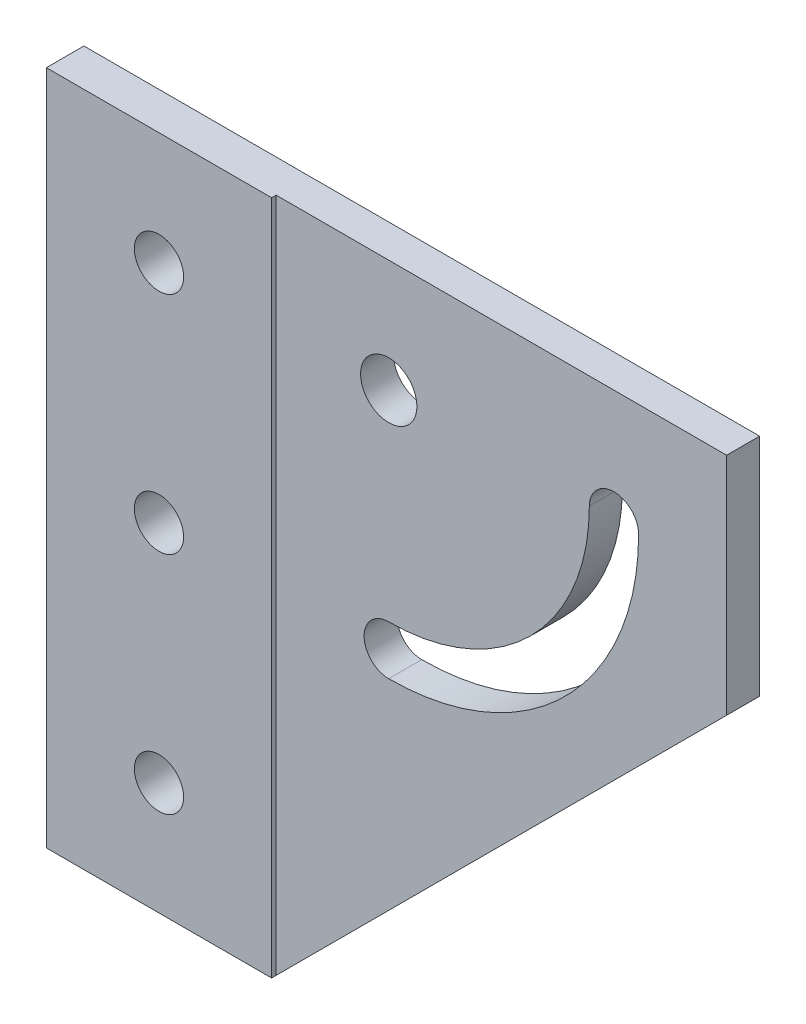
SolidWorks part; units mm, degrees
material "6105-T5 Aluminum"
ref_plane "Front Plane" through (0, 0, 0) normal (0, 0, 1) x (1, 0, 0)
ref_plane "Top Plane" through (0, 0, 0) normal (0, 1, 0) x (1, 0, 0)
ref_plane "Right Plane" through (0, 0, 0) normal (1, 0, 0) x (0, 0, -1)
ref_plane "Plane1" through (0, 0, -17.1983) normal (0, 0, -1) x (-1, 0, 0)
sketch "Sketch1" plane through (0, 0, -17.1983) normal (0, 0, -1) x (-1, 0, 0)
  line L0 (-47.8626, 85.0047) -> (-47.8626, 46.9047)
  line L1 (-47.8626, 46.9047) -> (28.3374, -29.2953)
  line L2 (28.3374, -29.2953) -> (66.4374, -29.2953)
  line L3 (66.4374, -29.2953) -> (66.4374, 85.0047)
  line L4 (66.4374, 85.0047) -> (-47.8626, 85.0047)
  dimension "D1" = 76.2
  dimension "D2" = 114.3
  dimension "D3" = 76.2
  dimension "D4" = 114.3
extrude "Boss-Extrude1" add sketch "Sketch1" against normal blind 5.588
sketch "Sketch2" plane through (0, 0, -11.6103) normal (0, 0, 1) x (1, 0, 0)
  line L0 (-66.4374, -29.2953) -> (-66.4374, 85.0047)
  line L1 (-66.4374, 85.0047) -> (-28.3374, 85.0047)
  line L2 (-28.3374, 85.0047) -> (-28.3374, -29.2953)
  line L3 (-28.3374, -29.2953) -> (-66.4374, -29.2953)
  line L4 (-66.4374, -29.2953) -> (-66.4374, 85.0047) construction
  line L5 (-28.3374, -29.2953) -> (-66.4374, -29.2953) construction
  dimension "D1" = 38.1
  dimension "D2" = 114.3
extrude "Boss-Extrude2" add sketch "Sketch2" along normal blind 0.762
sketch "Sketch3" plane through (0, 0, -11.6103) normal (0, 0, 1) x (1, 0, 0)
  line L0 (-28.3374, -29.2953) -> (-28.3374, 85.0047) construction
  arc A0 (-9.2874, 23.6891) -> (32.9782, 65.9547) centre (-9.2874, 65.9547) ccw
  arc A1 (32.9782, 65.9547) -> (24.647, 65.9547) centre (28.8126, 65.9547) ccw
  arc A2 (24.647, 65.9547) -> (-9.2874, 32.0203) centre (-9.2874, 65.9547) cw
  arc A3 (-9.2874, 32.0203) -> (-9.2874, 23.6891) centre (-9.2874, 27.8547) ccw
  dimension "D1" = 42.2656
  dimension "D2" = 4.1656
  dimension "D3" = 52.9844
  dimension "D4" = 52.9844
extrude "Cut-Extrude1" cut sketch "Sketch3" against normal through all
hole_wizard "Hole1" positions "Sketch5" profile "Sketch4" legacy
sketch "Sketch5" plane through (0, 0, -10.8483) normal (0, 0, 1) x (1, 0, 0)
  point P0 (-47.3874, -10.2453)
sketch "Sketch4" plane through (-47.3874, -10.2453, -10.8483) normal (1, 0, 0) x (0, -1, 0)
  line L0 (0, 0) -> (0, 6.35)
  line L1 (0, 6.35) -> (4.1656, 6.35)
  line L2 (4.1656, 6.35) -> (4.1656, 0)
  line L3 (4.1656, 0) -> (0, 0)
  line L4 (0, 110) -> (0, -10) construction
  dimension "Diameter" = 8.3312
  dimension "Depth" = 6.35
hole_wizard "Hole2" positions "Sketch7" profile "Sketch6" legacy
sketch "Sketch7" plane through (0, 0, -10.8483) normal (0, 0, 1) x (1, 0, 0)
  point P0 (-47.3874, 65.9547)
sketch "Sketch6" plane through (-47.3874, 65.9547, -10.8483) normal (1, 0, 0) x (0, -1, 0)
  line L0 (0, 0) -> (0, 6.35)
  line L1 (0, 6.35) -> (4.1656, 6.35)
  line L2 (4.1656, 6.35) -> (4.1656, 0)
  line L3 (4.1656, 0) -> (0, 0)
  line L4 (0, 110) -> (0, -10) construction
  dimension "Diameter" = 8.3312
  dimension "Depth" = 6.35
hole_wizard "Hole3" positions "Sketch9" profile "Sketch8" legacy
sketch "Sketch9" plane through (0, 0, -10.8483) normal (0, 0, 1) x (1, 0, 0)
  point P0 (-47.3874, 27.8547)
sketch "Sketch8" plane through (-47.3874, 27.8547, -10.8483) normal (1, 0, 0) x (0, -1, 0)
  line L0 (0, 0) -> (0, 6.35)
  line L1 (0, 6.35) -> (4.1656, 6.35)
  line L2 (4.1656, 6.35) -> (4.1656, 0)
  line L3 (4.1656, 0) -> (0, 0)
  line L4 (0, 110) -> (0, -10) construction
  dimension "Diameter" = 8.3312
  dimension "Depth" = 6.35
hole_wizard "M8 Clearance Hole1" positions "Sketch11" profile "Sketch10" hole size "M8" standard "Ansi Metric"
sketch "Sketch11" plane through (0, 0, -11.6103) normal (0, 0, 1) x (1, 0, 0)
  point P0 (-9.2874, 65.9547)
sketch "Sketch10" plane through (-9.2874, 65.9547, -11.6103) normal (1, 0, 0) x (0, -1, 0)
  line L0 (0, 0) -> (0, 5.588)
  line L1 (0, 5.588) -> (4.7625, 5.588)
  line L2 (4.7625, 5.588) -> (4.7625, 0)
  line L5 (4.7625, 0) -> (0, 0)
  line L11 (0, -6.35) -> (0, 107.95) construction
  dimension "Thru Hole Dia." = 9.525
  dimension "Thru Hole Depth" = 5.588
